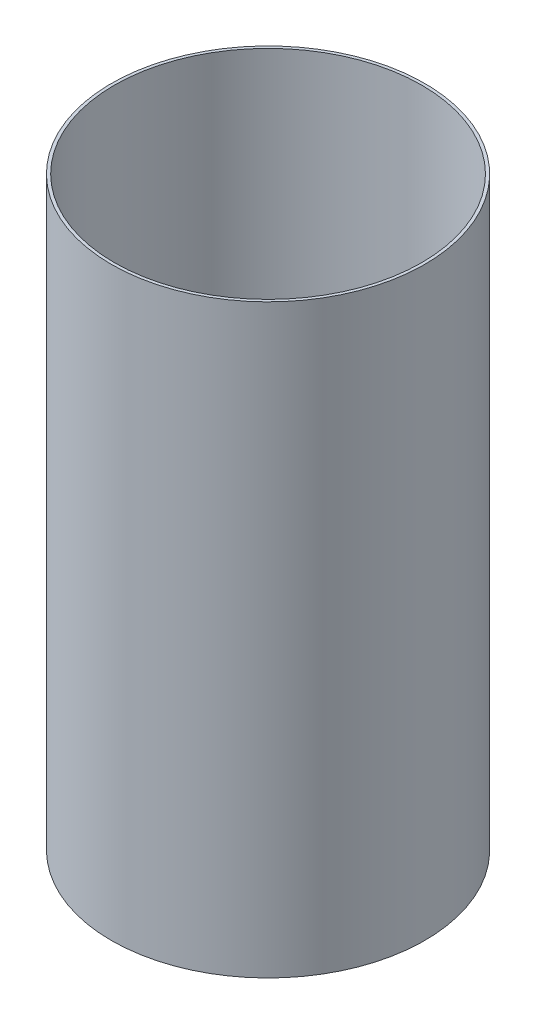
SolidWorks part; units mm, degrees
ref_plane "Front Plane" through (0, 0, 0) normal (0, 0, 1) x (1, 0, 0)
ref_plane "Top Plane" through (0, 0, 0) normal (0, 1, 0) x (1, 0, 0)
ref_plane "Right Plane" through (0, 0, 0) normal (1, 0, 0) x (0, 0, -1)
sketch "Sketch2" plane through (0, 0, 0) normal (0, 1, 0) x (1, 0, 0)
  circle A0 centre (0, 0) radius 74.7776
  circle A1 centre (0, 0) radius 73.3552
  dimension "D1" = 149.5552
  dimension "D2" = 1.4224
extrude "Boss-Extrude1" add sketch "Sketch2" along normal mid plane 279.4
equation "\"length\" = 11in"
equation "\"D1@Boss-Extrude1\"=\"length\""
